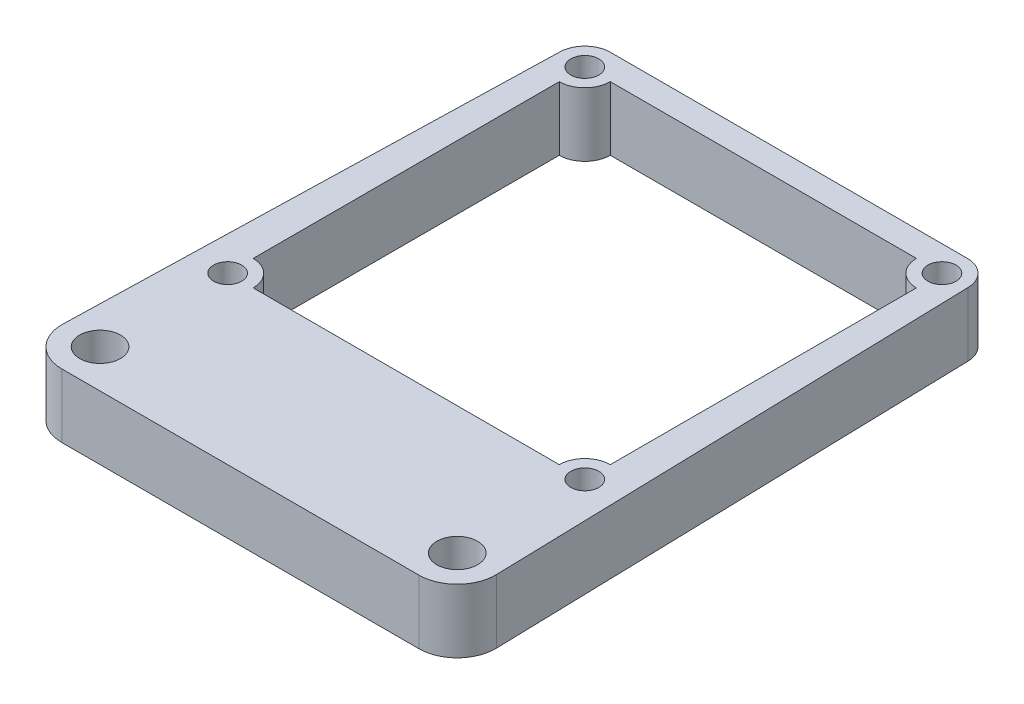
SolidWorks part; units mm, degrees
material "ABS"
ref_plane "正面" through (0, 0, 0) normal (0, 0, 1) x (1, 0, 0)
ref_plane "平面" through (0, 0, 0) normal (0, 1, 0) x (1, 0, 0)
ref_plane "右側面" through (0, 0, 0) normal (1, 0, 0) x (0, 0, -1)
sketch "ｽｹｯﾁ1" plane through (0, 0, 0) normal (0, 1, 0) x (1, 0, 0)
  line L0 (-14, -14) -> (-14, -24) construction
  line L1 (14, -14) -> (-14, -14) construction
  line L2 (14, -14) -> (14, 14) construction
  line L3 (14, 14) -> (-14, 14) construction
  line L4 (-14, -14) -> (-14, 14) construction
  line L5 (14, -14) -> (-14, 14) construction
  line L6 (14, 14) -> (-14, -14) construction
  line L7 (-14, -24) -> (14, -14) construction
  line L8 (14, -14) -> (14, -24) construction
  line L9 (14, -24) -> (-14, -24) construction
  line L10 (-14, 12) -> (-14, -12)
  line L11 (-12, -14) -> (12, -14)
  line L12 (14, -12) -> (14, 12)
  line L13 (12, 14) -> (-12, 14)
  line L14 (-15.9993, 14.0526) -> (-16.999, -23.9211)
  line L15 (0, 14) -> (0, -24) construction
  line L16 (15.9993, 14.0526) -> (16.999, -23.9211)
  line L17 (-14, 16) -> (14, 16)
  line L18 (-14, -27) -> (14, -27)
  circle A0 centre (-14, 14) radius 1.1
  circle A1 centre (14, 14) radius 1.1
  circle A2 centre (14, -14) radius 1.1
  circle A3 centre (-14, -14) radius 1.1
  circle A4 centre (-14, -24) radius 1.6
  circle A5 centre (14, -24) radius 1.6
  arc A6 (-14, 12) -> (-12, 14) centre (-14, 14) ccw
  arc A7 (12, 14) -> (14, 12) centre (14, 14) ccw
  arc A8 (14, -12) -> (12, -14) centre (14, -14) ccw
  arc A9 (-12, -14) -> (-14, -12) centre (-14, -14) ccw
  arc A10 (-14, 16) -> (-15.9993, 14.0526) centre (-14, 14) ccw
  arc A11 (-16.999, -23.9211) -> (-14, -27) centre (-14, -24) ccw
  arc A12 (16.999, -23.9211) -> (14, -27) centre (14, -24) cw
  arc A13 (14, 16) -> (15.9993, 14.0526) centre (14, 14) cw
  point P0 (0, 0)
  point P15 (0, 0)
  point P30 (0, 0)
  point P35 (-33.8174, -16.8725)
  dimension "D3" = 2.2
  dimension "D5" = 3.2
  dimension "D6" = 2
  dimension "D8" = 3
  dimension "D1" = 28
  dimension "D4" = 10
  dimension "D2" = 4
  dimension "D7" = 4
extrude "ﾎﾞｽ - 押し出し1" add sketch "ｽｹｯﾁ1" along normal blind 5
